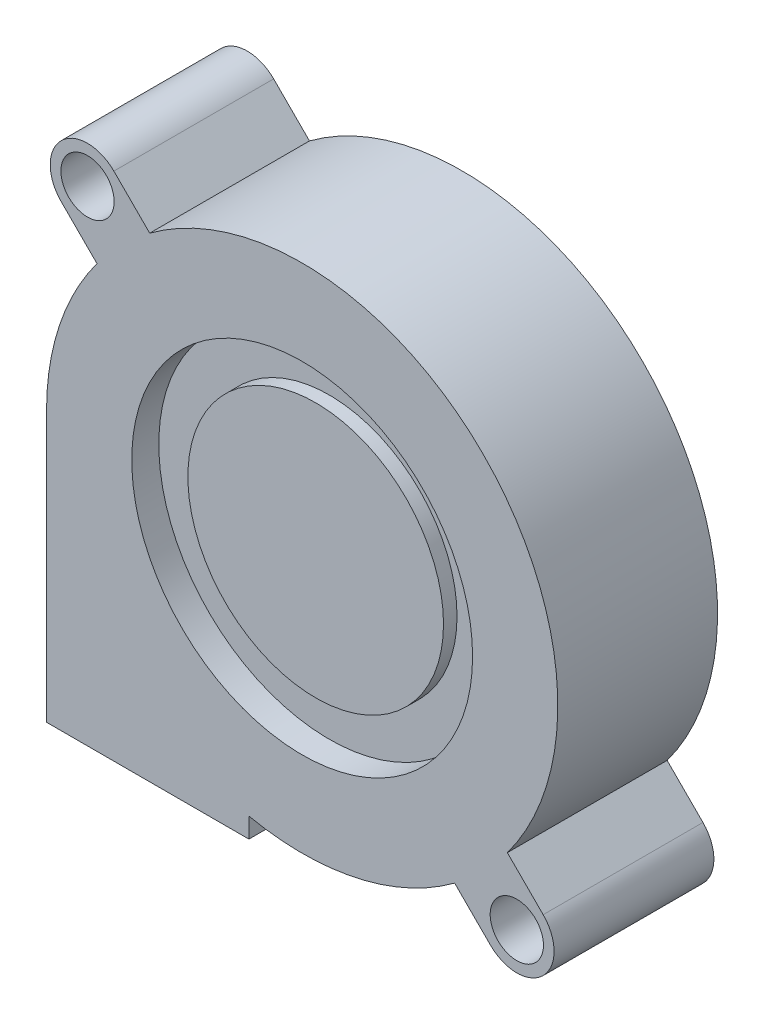
SolidWorks part; units mm, degrees
ref_plane "Front Plane" through (0, 0, 0) normal (0, 0, 1) x (1, 0, 0)
ref_plane "Top Plane" through (0, 0, 0) normal (0, 1, 0) x (1, 0, 0)
ref_plane "Right Plane" through (0, 0, 0) normal (1, 0, 0) x (0, 0, -1)
sketch "Sketch1" plane through (0, 0, 0) normal (0, 0, 1) x (1, 0, 0)
  line L0 (0, 0) -> (-22.6274, 22.6274)
  line L1 (0, 0) -> (22.6274, -22.6274)
  line L2 (-22.6274, 22.6274) -> (-21.9203, 21.9203)
  line L3 (22.6274, -22.6274) -> (21.9203, -21.9203)
  line L4 (0, 0) -> (-24, 0) construction
  line L5 (-20.1525, 20.1525) -> (-22.6274, 17.6777)
  line L6 (-22.6274, 17.6777) -> (17.6777, -22.6274)
  line L7 (17.6777, -22.6274) -> (22.6274, -17.6777)
  line L8 (22.6274, -17.6777) -> (-17.6777, 22.6274)
  line L9 (-24, 0) -> (-24, -25.3475)
  line L10 (-24, -25.3475) -> (-5, -25.3475)
  line L11 (-5, -25.3475) -> (-5, -23.4734)
  circle A0 centre (0, 0) radius 24
  circle A1 centre (-20.1525, 20.1525) radius 2.5
  circle A2 centre (20.1525, -20.1525) radius 2.5
  circle A3 centre (20.1525, -20.1525) radius 3.5
  circle A4 centre (-20.1525, 20.1525) radius 3.5
  dimension "D1" = 32
  dimension "D4" = 5
  dimension "D5" = 5
  dimension "D7" = 1
  dimension "D8" = 19
  dimension "D9" = 48
  dimension "D2" = 32
  dimension "D3" = 1
  dimension "D6" = 45
  dimension "D10" = 45.5
extrude "Boss-Extrude1" add sketch "Sketch1" along normal blind 15 contours A0 L9 L10 L11 | L6 L4 A0 | L4 L6 A0 | L4 L0 A0 L6 | L1 L4 L6 A0 | L8 A0 L0 L1 | L8 A0 | A4 L6 A0 L0 | A4 L0 A0 L8 | L7 A3 L1 A2 | L1 A3 L7 A2 | A3 L1 A0 L6 | A3 L8 A0 L1 | L7 A3 L1 A2 | L1 A3 L7 A2 | L0 A4 L5 A1 | A4 L0 A1 | L5 A4 L0 A1
sketch "Sketch2" plane through (0, -25.3475, 0) normal (0, -1, 0) x (1, 0, 0)
  line L1 (-6.2, 13.8) -> (-22.8, 13.8)
  line L2 (-22.8, 13.8) -> (-22.8, 1.2)
  line L3 (-22.8, 1.2) -> (-6.2, 1.2)
  line L4 (-6.2, 1.2) -> (-6.2, 13.8)
  line L5 (-24, 0) -> (-5, 0)
  line L6 (-5, 0) -> (-5, 15)
  line L7 (-5, 15) -> (-24, 15)
  line L8 (-24, 15) -> (-24, 0)
  line L9 (-24, 0) -> (-5, 0)
  line L10 (-5, 0) -> (-5, 15)
  line L11 (-5, 15) -> (-24, 15)
  line L12 (-24, 15) -> (-24, 0)
  dimension "D1" = 0
  dimension "D2" = 1.2
extrude "Cut-Extrude1" cut sketch "Sketch2" against normal blind 4 contours L3 L4 L1 L2
sketch "Sketch3" plane through (0, 0, 15) normal (0, 0, 1) x (1, 0, 0)
  circle A0 centre (0, 0) radius 16
  circle A1 centre (0, 0) radius 12
extrude "Cut-Extrude2" cut sketch "Sketch3" against normal blind 2.54
sketch "Sketch4" plane through (0, 0, 15) normal (0, 0, 1) x (1, 0, 0)
  circle A1 centre (0, 0) radius 12
  circle A2 centre (0, 0) radius 12
  dimension "D1" = 0
extrude "Cut-Extrude3" cut sketch "Sketch4" against normal blind 1.27
